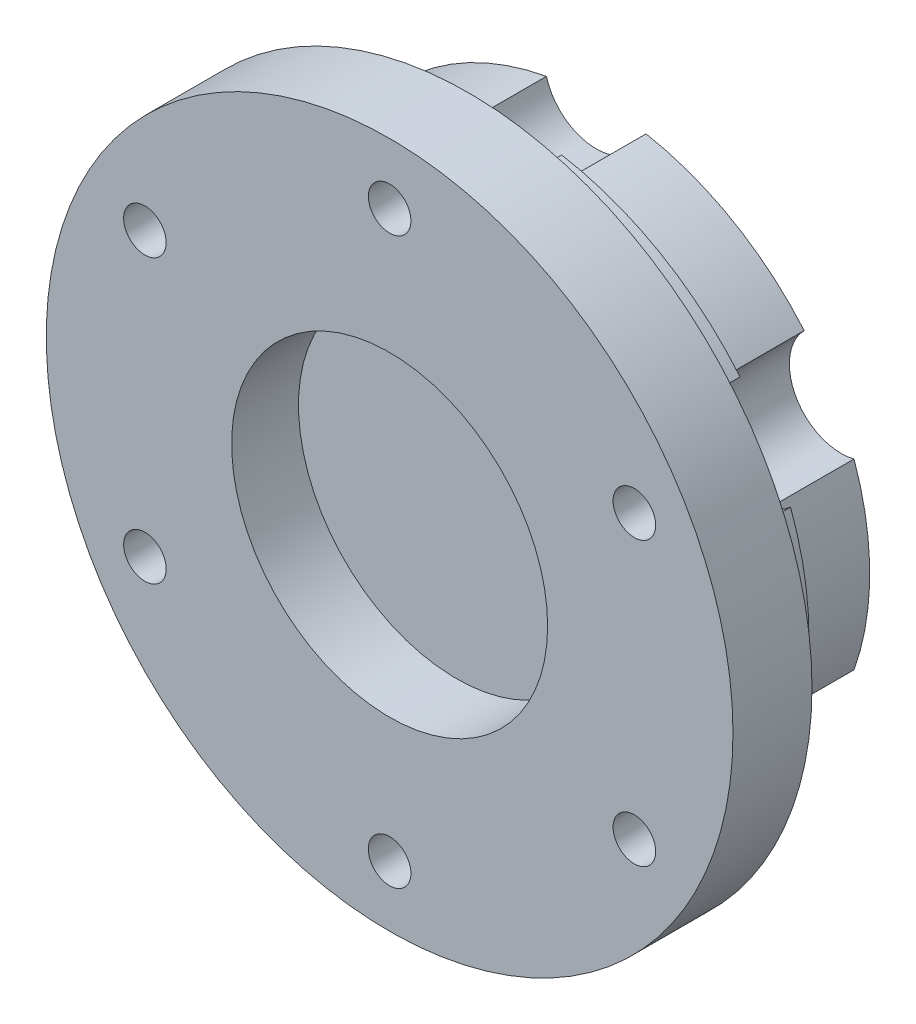
SolidWorks part; units mm, degrees
ref_plane "Front Plane" through (0, 0, 0) normal (0, 0, 1) x (1, 0, 0)
ref_plane "Top Plane" through (0, 0, 0) normal (0, 1, 0) x (1, 0, 0)
ref_plane "Right Plane" through (0, 0, 0) normal (1, 0, 0) x (0, 0, -1)
sketch "Sketch1" plane through (0, 0, 0) normal (1, 0, 0) x (0, 0, -1)
  line L0 (0, 0) -> (79.2027, 0) construction
  line L1 (0, 0) -> (0, 28.25)
  line L2 (0, 28.25) -> (6.5, 28.25)
  line L3 (6.5, 28.25) -> (6.5, 24.5)
  line L4 (6.5, 24.5) -> (10, 24.5)
  line L5 (10, 24.5) -> (10, 22.5)
  line L6 (10, 22.5) -> (17, 22.5)
  line L7 (17, 22.5) -> (17, 0)
  line L8 (17, 0) -> (0, 0)
  dimension "D1" = 28.25
  dimension "D2" = 6.5
  dimension "D3" = 3.5
  dimension "18" = 7
  dimension "D4" = 22.5
  dimension "D5" = 2
revolve "Revolve1" add sketch "Sketch1" angle 360 about L0
sketch "Sketch2" plane through (0, 0, -6.5) normal (0, 0, -1) x (-1, 0, 0)
  line L0 (0, 0) -> (0, 28.25) construction
  circle A0 centre (0, 0) radius 28.25 construction
  circle A1 centre (0, 23.25) radius 1.75
  dimension "D1" = 3.5
  dimension "D2" = 23.25
extrude "Cut-Extrude1" cut sketch "Sketch2" against normal through all both and the other way through all
pattern_circular "CirPattern1" count 6 over 360 about axis through (0, 0, 0) along (0, 0, 1) of "Cut-Extrude1"
sketch "Sketch5" plane through (0, 0, -17) normal (0, 0, -1) x (-1, 0, 0)
  line L0 (0, 0) -> (11.25, 19.4856) construction
  line L1 (0, 0) -> (0, 23.25) construction
  circle A0 centre (0, 0) radius 16.5 construction
  arc A1 (-1.5545, 22.4462) -> (-18.6618, 12.5694) centre (0, 0) ccw
  circle A3 centre (8.25, 14.2894) radius 1.75
  arc A16 (-1.5545, 22.4462) -> (-18.6618, 12.5694) centre (0, 0) ccw
  arc A17 (-20.2163, 9.8769) -> (-18.6618, 12.5694) centre (-20.1351, 11.625) ccw
  arc A18 (-20.2163, 9.8769) -> (-18.6618, 12.5694) centre (-20.1351, 11.625) ccw
  arc A19 (-20.2163, 9.8769) -> (-20.2163, -9.8769) centre (0, 0) ccw
  arc A20 (-20.2163, 9.8769) -> (-20.2163, -9.8769) centre (0, 0) ccw
  arc A21 (-18.6618, -12.5694) -> (-20.2163, -9.8769) centre (-20.1351, -11.625) ccw
  arc A22 (-18.6618, -12.5694) -> (-20.2163, -9.8769) centre (-20.1351, -11.625) ccw
  arc A23 (-18.6618, -12.5694) -> (-1.5545, -22.4462) centre (0, 0) ccw
  arc A24 (-18.6618, -12.5694) -> (-1.5545, -22.4462) centre (0, 0) ccw
  arc A25 (1.5545, -22.4462) -> (-1.5545, -22.4462) centre (0, -23.25) ccw
  arc A26 (1.5545, -22.4462) -> (-1.5545, -22.4462) centre (0, -23.25) ccw
  arc A27 (1.5545, -22.4462) -> (18.6618, -12.5694) centre (0, 0) ccw
  arc A28 (1.5545, -22.4462) -> (18.6618, -12.5694) centre (0, 0) ccw
  arc A29 (20.2163, -9.8769) -> (18.6618, -12.5694) centre (20.1351, -11.625) ccw
  arc A30 (20.2163, -9.8769) -> (18.6618, -12.5694) centre (20.1351, -11.625) ccw
  arc A31 (20.2163, -9.8769) -> (20.2163, 9.8769) centre (0, 0) ccw
  arc A32 (20.2163, -9.8769) -> (20.2163, 9.8769) centre (0, 0) ccw
  arc A33 (18.6618, 12.5694) -> (20.2163, 9.8769) centre (20.1351, 11.625) ccw
  arc A34 (18.6618, 12.5694) -> (20.2163, 9.8769) centre (20.1351, 11.625) ccw
  arc A35 (18.6618, 12.5694) -> (1.5545, 22.4462) centre (0, 0) ccw
  arc A36 (18.6618, 12.5694) -> (1.5545, 22.4462) centre (0, 0) ccw
  arc A37 (-1.5545, 22.4462) -> (1.5545, 22.4462) centre (0, 23.25) ccw
  arc A38 (-1.5545, 22.4462) -> (1.5545, 22.4462) centre (0, 23.25) ccw
  dimension "D3" = 3.5
  dimension "D2" = 6
  dimension "D4" = 30
extrude "Cut-Extrude2" cut sketch "Sketch5" against normal blind 10 contours A3
pattern_circular "CirPattern2" count 6 over 360 about axis through (0, 0, 0) along (0, 0, 1) of "Cut-Extrude2"
sketch "Sketch6" plane through (0, 0, 0) normal (0, 0, 1) x (1, 0, 0)
  circle A0 centre (0, 0) radius 13
  dimension "D1" = 26
extrude "Cut-Extrude3" cut sketch "Sketch6" against normal blind 5.5
sketch "Sketch7" plane through (0, 0, -6.5) normal (0, 0, -1) x (-1, 0, 0)
  circle A0 centre (-20.1351, 11.625) radius 1.75 construction
  circle A1 centre (-20.1351, 11.625) radius 1.75
  circle A2 centre (-20.1351, 11.625) radius 4.25
  dimension "D1" = 2.5
extrude "Cut-Extrude4" cut sketch "Sketch7" along normal through all
pattern_circular "CirPattern3" count 6 over 360 about axis through (0, 0, 0) along (0, 0, 1) of "Cut-Extrude4"
hole_wizard "CSK for M3 Flat Head Machine Screw1" positions "Sketch8" profile "Sketch9" countersink size "M3" standard "ANSI Metric" end condition up to next
sketch "Sketch8" plane through (0, 0, -6.5) normal (0, 0, -1) x (-1, 0, 0)
  point P0 (-20.1351, 11.625)
  point P3 (0, -23.25)
  point P6 (0, -23.25)
  point P9 (20.1351, 11.625)
  point P12 (0, 23.25)
  point P15 (20.1351, -11.625)
  point P18 (-20.1351, -11.625)
sketch "Sketch9" plane through (20.1351, 11.625, -6.5) normal (1, 0, 0) x (0, 1, 0)
  line L0 (0, 0) -> (0, 6.5)
  line L1 (0, 6.5) -> (1.7, 6.5)
  line L2 (1.7, 6.5) -> (1.7, 1.45)
  line L3 (1.7, 1.45) -> (3.15, 0)
  line L5 (3.15, 0) -> (0, 0)
  line L6 (-1.7, 1.45) -> (-3.15, 0) construction
  line L11 (0, -6.35) -> (0, 107.95) construction
  dimension "Thru Hole Dia." = 3.4
  dimension "Thru Hole Depth" = 6.5
  dimension "Near C'Sink Dia." = 6.3
  dimension "Near C'Sink Angle" = 90
equation "\"Module\"= 1.5mm"
equation "\"Number of teeth\"= 15"
equation "\"Internal Bearing 'r'\"= 2.5mm"
equation "\"External Bearing 'r'\"= 13mm"
equation "\"Bearing Depth\"= 5mm"
equation "\"Planet Path Radius\"= 10.5mm + ( ( \"Number of teeth\" + 2 ) * \"Module\" ) / 2"
equation "\"Pin Radius\"= 4mm"
equation "\"Fastening Holes\"= 3mm"
equation "\"D1@Sketch1\"=\"Planet Path Radius\" + 5"
equation "\"D1@Sketch2\"=\"Fastening Holes\"+0.5"
equation "\"D2@Sketch2\"=\"Planet Path Radius\""
equation "\"Number of Planets\"= 3"
equation "\"D3@Sketch5\"=\"Fastening Holes\" +0.5"
equation "\"D1@Sketch6\"=\"External Bearing 'r'\"*2''''''''''''''''''''''''"
equation "\"D1@Cut-Extrude3\"=\"Bearing Depth\"+.5"
equation "\"Big Bearing E.R.\"= 29mm"
equation "\"Big Bearing I.R.\"= 22.5mm"
equation "\"D4@Sketch1\"=\"Big Bearing I.R.\""
